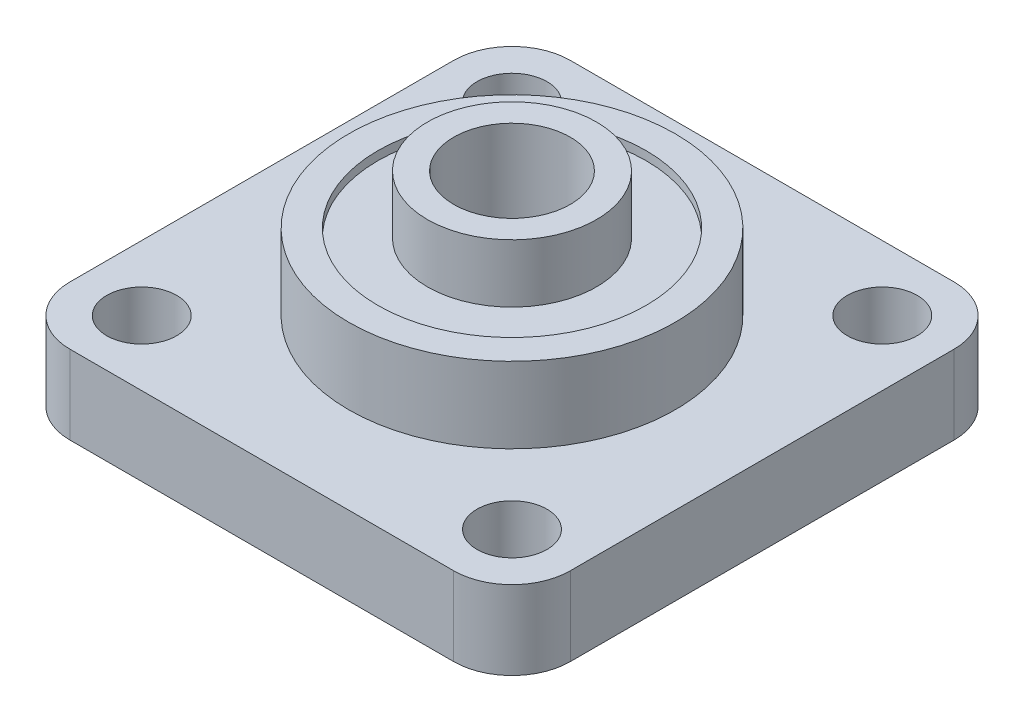
SolidWorks part; units mm, degrees
ref_plane "前视基准面" through (0, 0, 0) normal (0, 0, 1) x (1, 0, 0)
ref_plane "上视基准面" through (0, 0, 0) normal (0, 1, 0) x (1, 0, 0)
ref_plane "右视基准面" through (0, 0, 0) normal (1, 0, 0) x (0, 0, -1)
sketch "草图1" plane through (0, 0, 0) normal (0, 0, 1) x (1, 0, 0)
  line L0 (0, 50.9425) -> (0, 0) construction
  line L1 (0, 0) -> (58.6416, 0) construction
  line L2 (10, 30) -> (14.5, 30)
  line L3 (14.5, 30) -> (14.5, 20)
  line L4 (14.5, 20) -> (23, 20)
  line L5 (23, 20) -> (23, 21.5)
  line L6 (23, 21.5) -> (28, 21.5)
  line L7 (28, 21.5) -> (28, 3.5)
  line L8 (28, 3.5) -> (14.5, 3.5)
  line L9 (14.5, 3.5) -> (14.5, 0)
  line L10 (14.5, 0) -> (10, 0)
  line L11 (10, 0) -> (10, 30)
  point P6 (28, 12.5)
  dimension "D1" = 14.5
  dimension "D2" = 10
  dimension "D3" = 8.5
  dimension "D4" = 28
  dimension "D5" = 10
  dimension "D6" = 30
  dimension "D7" = 3.5
  dimension "D8" = 5
revolve "旋转1" add sketch "草图1" angle 360 about L0
ref_plane "基准面1" through (0, -5, 0) normal (0, 1, 0) x (1, 0, 0)
sketch "草图2" plane through (0, -5, 0) normal (0, 1, 0) x (1, 0, 0)
  line L1 (-42.9, 42.9) -> (42.9, 42.9)
  line L2 (-42.9, 42.9) -> (-42.9, -42.9)
  line L3 (-42.9, -42.9) -> (42.9, -42.9)
  line L4 (42.9, 42.9) -> (42.9, -42.9)
  line L5 (-42.9, 42.9) -> (42.9, -42.9) construction
  line L6 (-42.9, -42.9) -> (42.9, 42.9) construction
  circle A0 centre (-31.75, 31.75) radius 6
  circle A1 centre (31.75, 31.75) radius 6
  circle A2 centre (31.75, -31.75) radius 6
  circle A3 centre (-31.75, -31.75) radius 6
  point P0 (0, 0)
  dimension "D2" = 12
  dimension "D4" = 63.5
  dimension "D1" = 85.8
  dimension "D3" = 4
extrude "凸台-拉伸1" add sketch "草图2" along normal blind 13.5
fillet "圆角1" radius 10 4 edges at (42.9, 1.75, 42.9) (42.9, 1.75, -42.9) (-42.9, 1.75, -42.9) (-42.9, 1.75, 42.9)
sketch "草图3" plane through (0, 8.5, 0) normal (0, 1, 0) x (1, 0, 0)
  circle A1 centre (0, 0) radius 10
  circle A2 centre (0, 0) radius 10
  dimension "D1" = 0
extrude "切除-拉伸1" cut sketch "草图3" against normal through all
